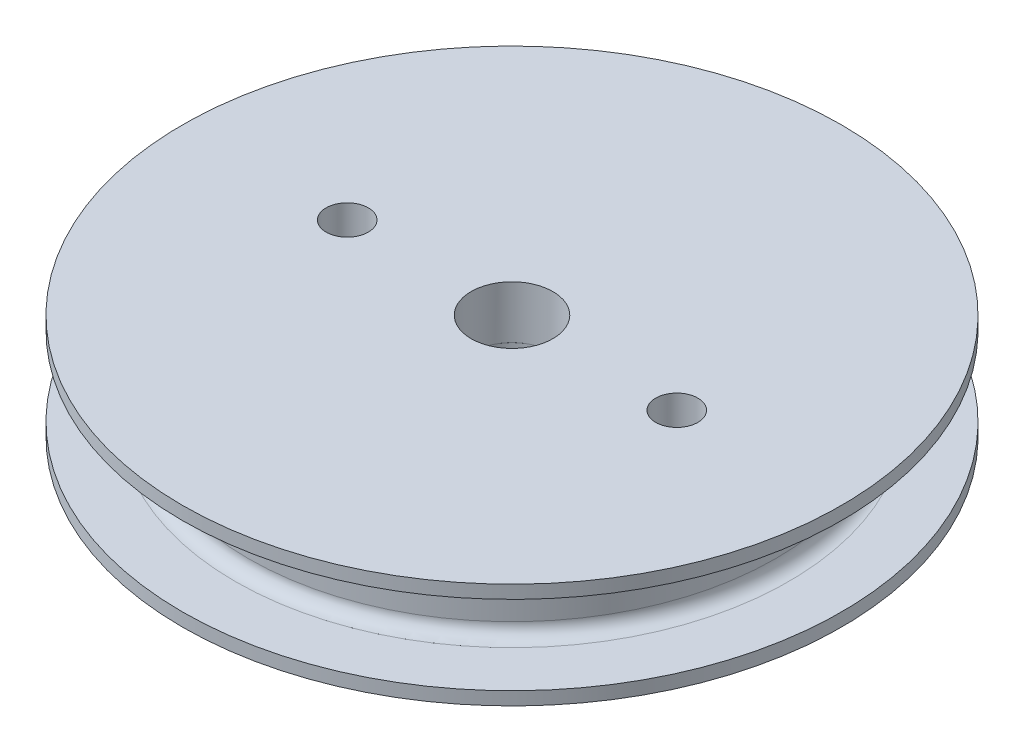
SolidWorks part; units mm, degrees
ref_plane "正面" through (0, 0, 0) normal (0, 0, 1) x (1, 0, 0)
ref_plane "平面" through (0, 0, 0) normal (0, 1, 0) x (1, 0, 0)
ref_plane "右側面" through (0, 0, 0) normal (1, 0, 0) x (0, 0, -1)
sketch "ｽｹｯﾁ1" plane through (0, 0, 0) normal (0, 0, 1) x (1, 0, 0)
  line L0 (0, 0) -> (0, 4)
  line L1 (0, 4) -> (20, 4)
  line L3 (25, 0) -> (0, 0)
  line L5 (20, 4) -> (20, 2)
  line L6 (21, 1) -> (25, 1)
  line L7 (25, 1) -> (25, 0)
  arc A1 (20, 2) -> (21, 1) centre (21, 2) ccw
  point P11 (20, 1)
  dimension "D5" = 1
  dimension "D1" = 3
  dimension "D2" = 5
  dimension "D3" = 20
  dimension "D4" = 1
revolve "回転1" add sketch "ｽｹｯﾁ1" angle 360 about L0
mirror "ﾐﾗｰ1" about plane through (0, 4, 0) normal (0, 1, 0) of bodies 101
sketch "ｽｹｯﾁ2" plane through (0, 8, 0) normal (0, 1, 0) x (1, 0, 0)
  circle A0 centre (0, 0) radius 3.1
  dimension "D1" = 6.2
extrude "ｶｯﾄ - 押し出し1" cut sketch "ｽｹｯﾁ2" against normal through all
sketch "ｽｹｯﾁ3" plane through (0, 0, 0) normal (0, -1, 0) x (1, 0, 0)
  line L0 (0, 0) -> (12.5, 0) construction
  line L1 (-12.5, 0) -> (0, 0) construction
  circle A0 centre (12.5, 0) radius 1.6
  circle A1 centre (-12.5, 0) radius 1.6
  point P5 (0, 0)
  point P6 (0, 0)
  point P8 (0, 0)
  dimension "D1" = 3.2
  dimension "D3" = 25
  dimension "D2" = 2
extrude "ｶｯﾄ - 押し出し2" cut sketch "ｽｹｯﾁ3" against normal through all
